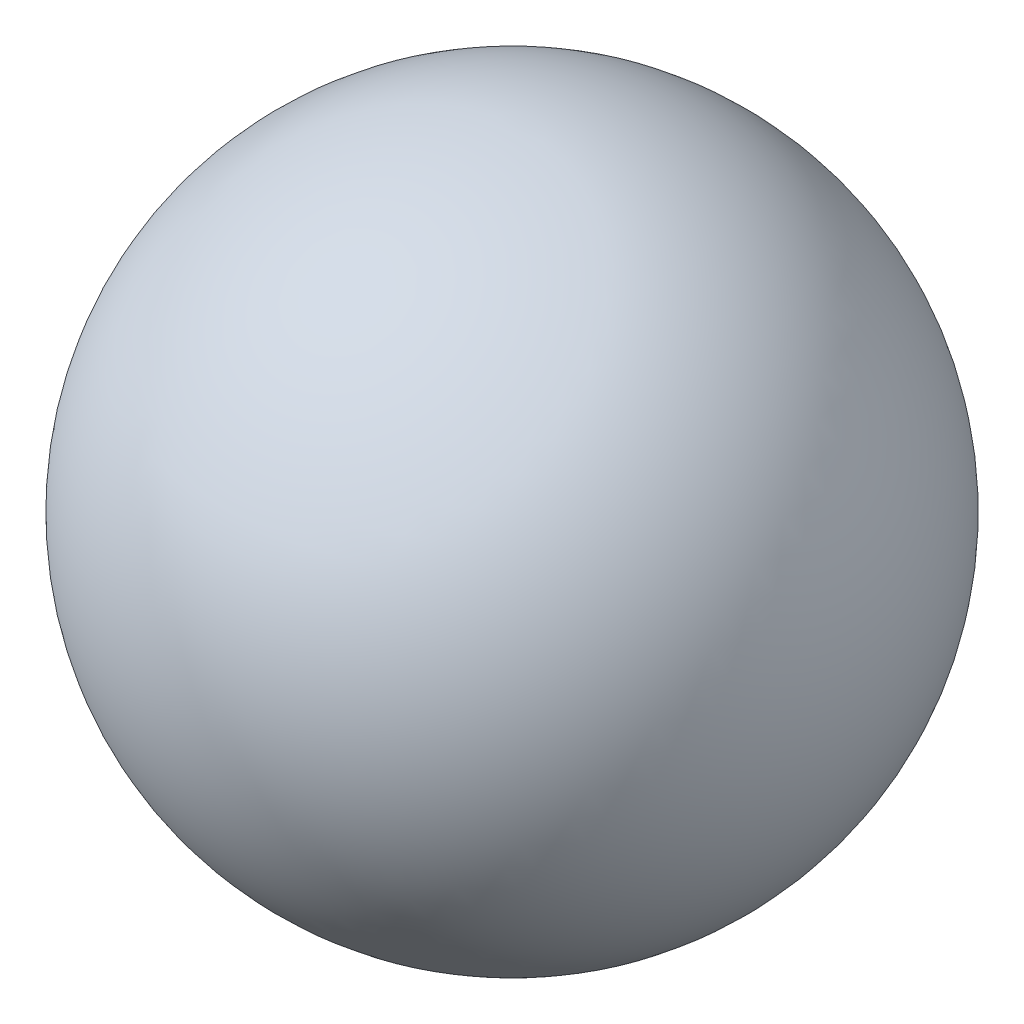
SolidWorks part; units mm, degrees
ref_plane "Front Plane" through (0, 0, 0) normal (0, 0, 1) x (1, 0, 0)
ref_plane "Top Plane" through (0, 0, 0) normal (0, 1, 0) x (1, 0, 0)
ref_plane "Right Plane" through (0, 0, 0) normal (1, 0, 0) x (0, 0, -1)
sketch "Sketch1" plane through (0, 0, 0) normal (0, 0, 1) x (1, 0, 0)
  line L0 (0, 7.493) -> (0, -7.493)
  arc A0 (0, 7.493) -> (0, -7.493) centre (0, 0) cw
  dimension "D1" = 14.986
revolve "Revolve1" add sketch "Sketch1" angle 360 about L0
